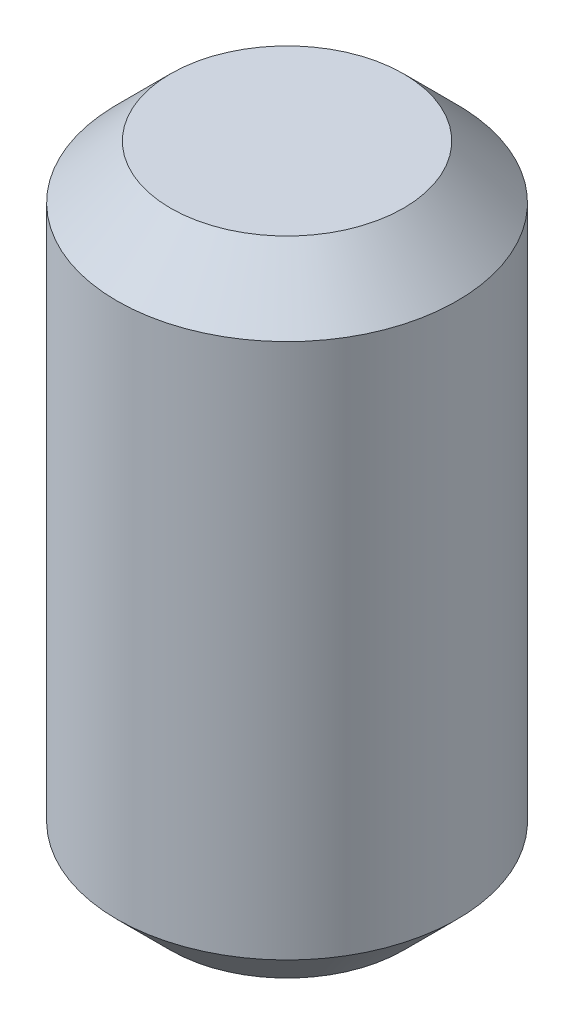
SolidWorks part; units mm, degrees
ref_plane "Спереди" through (0, 0, 0) normal (0, 0, 1) x (1, 0, 0)
ref_plane "Сверху" through (0, 0, 0) normal (0, 1, 0) x (1, 0, 0)
ref_plane "Справа" through (0, 0, 0) normal (1, 0, 0) x (0, 0, -1)
other "Configuration Table"
sketch "Эскиз1" plane through (0, 0, 0) normal (0, 1, 0) x (1, 0, 0)
  circle A0 centre (0, 0) radius 1.5875
  dimension "D1" = 3.175
extrude "Бобышка-Вытянуть1" add sketch "Эскиз1" along normal blind 6
chamfer "Фаска1" distance 0.5 angle 45 2 edges at (0, 0, 1.5875) (0, 6, 1.5875)
